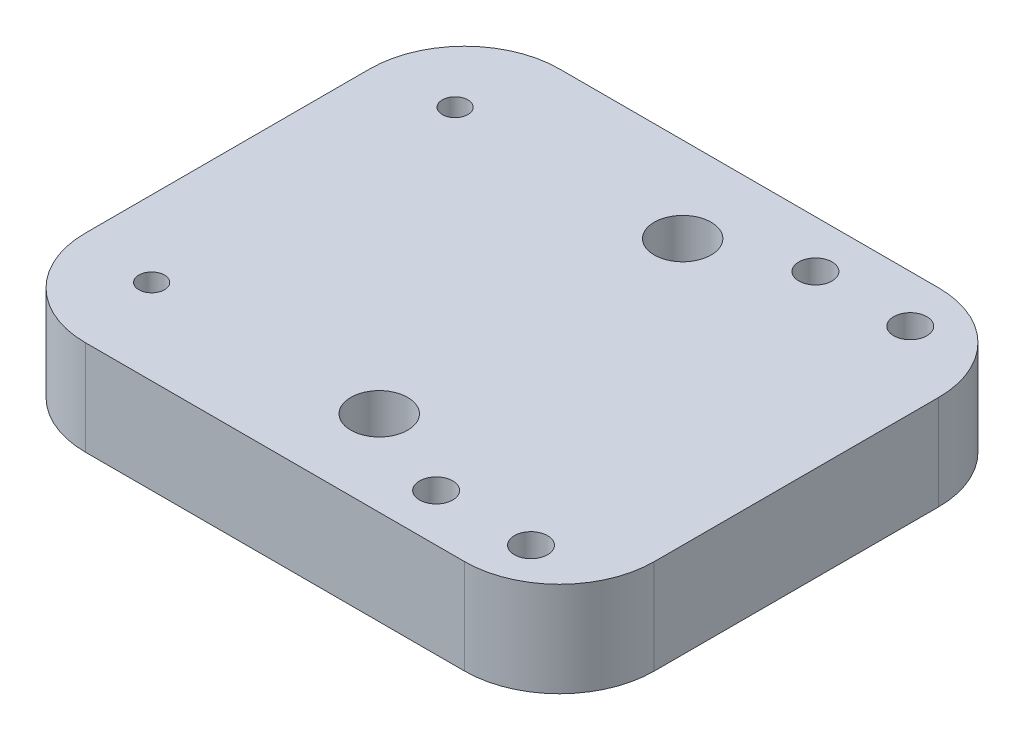
SolidWorks part; units mm, degrees
ref_plane "Front Plane" through (0, 0, 0) normal (0, 0, 1) x (1, 0, 0)
ref_plane "Top Plane" through (0, 0, 0) normal (0, 1, 0) x (1, 0, 0)
ref_plane "Right Plane" through (0, 0, 0) normal (1, 0, 0) x (0, 0, -1)
sketch "Sketch1" plane through (0, 0, 0) normal (0, 1, 0) x (1, 0, 0)
  line L1 (0, 0) -> (60, 0)
  line L2 (0, 0) -> (0, 50)
  line L3 (0, 50) -> (60, 50)
  line L4 (60, 0) -> (60, 50)
  dimension "D1" = 60
  dimension "D2" = 50
extrude "Boss-Extrude1" add sketch "Sketch1" along normal blind 10
sketch "Sketch2" plane through (0, 10, 0) normal (0, 1, 0) x (1, 0, 0)
  line L0 (8, 41) -> (8, 50) construction
  line L1 (60, 50) -> (0, 50) construction
  line L2 (8, 9) -> (8, 0) construction
  line L3 (0, 0) -> (60, 0) construction
  line L4 (0, 50) -> (0, 0) construction
  circle A0 centre (8, 41) radius 1.35
  circle A1 centre (8, 9) radius 1.35
  circle A2 centre (32, 9) radius 1.35
  circle A3 centre (32, 41) radius 1.35
  point P0 (8, 41)
  point P1 (32, 41)
  point P2 (8, 9)
  point P3 (32, 9)
  dimension "D4" = 2.7
  dimension "D1" = 24
  dimension "D2" = 32
  dimension "D3" = 8
extrude "Cut-Extrude1" cut sketch "Sketch2" against normal through all
sketch "Sketch3" plane through (0, 10, 0) normal (0, 1, 0) x (1, 0, 0)
  line L0 (52, 45) -> (52, 50) construction
  line L2 (60, 50) -> (0, 50) construction
  line L5 (52, 5) -> (52, 0) construction
  line L6 (0, 0) -> (60, 0) construction
  line L7 (60, 0) -> (60, 50) construction
  circle A0 centre (42, 45) radius 1.75
  circle A1 centre (52, 45) radius 1.75
  circle A2 centre (52, 5) radius 1.75
  circle A3 centre (42, 5) radius 1.75
  point P8 (0, 0)
  point P10 (69.6087, 0)
  point P14 (69.6562, -0.5699)
  point P15 (0, 0)
  dimension "D1" = 3.5
  dimension "D2" = 8
  dimension "D3" = 40
  dimension "D4" = 10
extrude "Cut-Extrude2" cut sketch "Sketch3" against normal through all contours A0
fillet "Fillet1" radius 10 4 edges at (0, 5, 0) (60, 5, 0) (60, 5, -50) (0, 5, -50)
sketch "Sketch4" plane through (0, 10, 0) normal (0, 1, 0) x (1, 0, 0)
  circle A0 centre (32, 41) radius 3
  circle A1 centre (32, 9) radius 3
  dimension "D1" = 6
extrude "Cut-Extrude3" cut sketch "Sketch4" against normal blind 5
